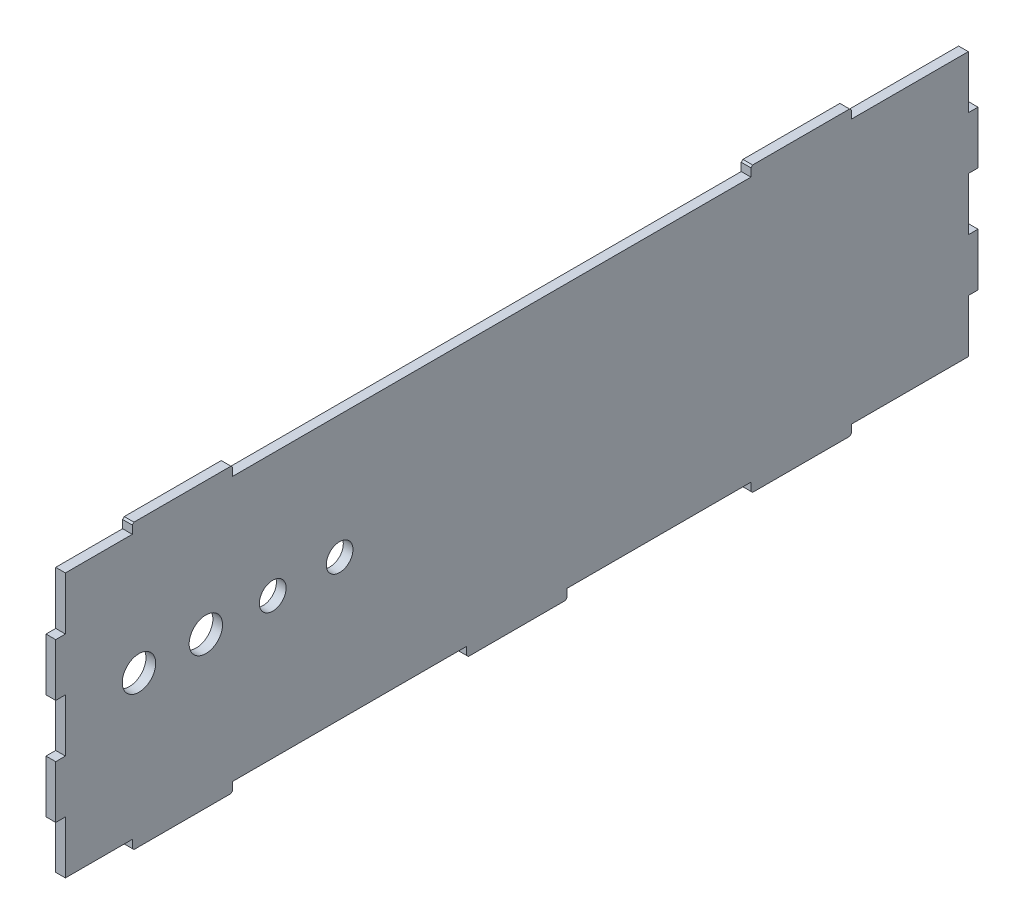
SolidWorks part; units mm, degrees
material "Acrylic (Medium-high impact)"
ref_plane "Front Plane" through (0, 0, 0) normal (0, 0, 1) x (1, 0, 0)
ref_plane "Top Plane" through (0, 0, 0) normal (0, 1, 0) x (1, 0, 0)
ref_plane "Right Plane" through (0, 0, 0) normal (1, 0, 0) x (0, 0, -1)
ref_plane "Plane1" through (116, 0, 0) normal (1, 0, 0) x (0, 0, -1)
sketch "Sketch1" plane through (116, 0, 0) normal (1, 0, 0) x (0, 0, -1)
  line L0 (-135, 2.9) -> (-115, 2.9)
  line L1 (-115, 2.9) -> (-115, 0.5)
  line L2 (-115, 0.5) -> (-114.5, 0)
  line L3 (-114.5, 0) -> (-85.5, 0)
  line L4 (-85.5, 0) -> (-85, 0.5)
  line L5 (-85, 0.5) -> (-85, 2.9)
  line L6 (-85, 2.9) -> (-15, 2.9)
  line L7 (-15, 2.9) -> (-15, 0.5)
  line L8 (-15, 0.5) -> (-14.5, 0)
  line L9 (-14.5, 0) -> (14.5, 0)
  line L10 (14.5, 0) -> (15, 0.5)
  line L11 (15, 0.5) -> (15, 2.9)
  line L12 (15, 2.9) -> (70, 2.9)
  line L13 (70, 2.9) -> (70, 0.5)
  line L14 (70, 0.5) -> (70.5, 0)
  line L15 (70.5, 0) -> (99.5, 0)
  line L16 (99.5, 0) -> (100, 0.5)
  line L17 (100, 0.5) -> (100, 2.9)
  line L18 (100, 2.9) -> (135, 2.9)
  line L19 (135, 2.9) -> (135, 18.725)
  line L20 (135, 18.725) -> (137.9, 18.725)
  line L21 (137.9, 18.725) -> (137.9, 34.475)
  line L22 (137.9, 34.475) -> (135, 34.475)
  line L23 (135, 34.475) -> (135, 50.325)
  line L24 (135, 50.325) -> (137.9, 50.325)
  line L25 (137.9, 50.325) -> (137.9, 66.075)
  line L26 (137.9, 66.075) -> (135, 66.075)
  line L27 (135, 66.075) -> (135, 81.9)
  line L28 (135, 81.9) -> (100, 81.9)
  line L29 (100, 81.9) -> (100, 84.3)
  line L30 (100, 84.3) -> (99.5, 84.8)
  line L31 (99.5, 84.8) -> (70.5, 84.8)
  line L32 (70.5, 84.8) -> (70, 84.3)
  line L33 (70, 84.3) -> (70, 81.9)
  line L34 (70, 81.9) -> (-85, 81.9)
  line L35 (-85, 81.9) -> (-85, 84.3)
  line L36 (-85, 84.3) -> (-85.5, 84.8)
  line L37 (-85.5, 84.8) -> (-114.5, 84.8)
  line L38 (-114.5, 84.8) -> (-115, 84.3)
  line L39 (-115, 84.3) -> (-115, 81.9)
  line L40 (-115, 81.9) -> (-135, 81.9)
  line L41 (-135, 81.9) -> (-135, 66.075)
  line L42 (-135, 66.075) -> (-137.9, 66.075)
  line L43 (-137.9, 66.075) -> (-137.9, 50.325)
  line L44 (-137.9, 50.325) -> (-135, 50.325)
  line L45 (-135, 50.325) -> (-135, 34.475)
  line L46 (-135, 34.475) -> (-137.9, 34.475)
  line L47 (-137.9, 34.475) -> (-137.9, 18.725)
  line L48 (-137.9, 18.725) -> (-135, 18.725)
  line L49 (-135, 18.725) -> (-135, 2.9)
  circle A0 centre (-113, 45) radius 5
  circle A1 centre (-93, 45) radius 5
  circle A2 centre (-73, 45) radius 4
  circle A3 centre (-53, 45) radius 4
extrude "Boss-Extrude1" add sketch "Sketch1" along normal blind 2.9
